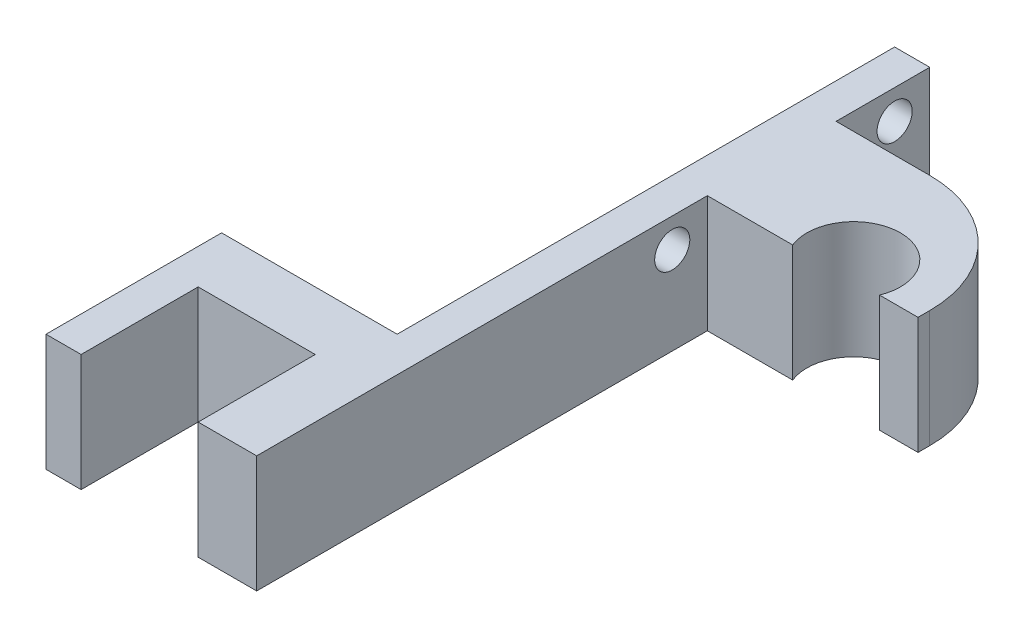
SolidWorks part; units mm, degrees
ref_plane "Front Plane" through (0, 0, 0) normal (0, 0, 1) x (1, 0, 0)
ref_plane "Top Plane" through (0, 0, 0) normal (0, 1, 0) x (1, 0, 0)
ref_plane "Right Plane" through (0, 0, 0) normal (1, 0, 0) x (0, 0, -1)
sketch "Sketch1" plane through (0, 0, 0) normal (0, 1, 0) x (1, 0, 0)
  line L0 (0, 0) -> (0, 34)
  line L1 (5, 34.5) -> (23, 34.5)
  line L2 (23, 23.5) -> (23, 34.5)
  line L3 (23, 23.5) -> (5, 23.5)
  line L4 (5, 23.5) -> (5, -15)
  line L5 (5, -15) -> (0, -15)
  line L6 (0, -15) -> (0, -5)
  line L7 (0, -5) -> (-10, -5)
  line L8 (-10, -5) -> (-10, -15)
  line L9 (-10, -15) -> (-13, -15)
  line L10 (-13, -15) -> (-13, 0)
  line L11 (-13, 0) -> (0, 0)
  line L12 (23, 29) -> (0, 29) construction
  line L13 (5, 23.5) -> (5, 42.5) construction
  line L14 (5, 42.5) -> (0, 42.5) construction
  line L15 (0, 42.5) -> (0, 34) construction
  line L16 (5, 34.5) -> (5, 42.5)
  line L17 (5, 42.5) -> (0, 42.5)
  line L18 (0, 42.5) -> (0, 34)
  dimension "D1" = 10
  dimension "D2" = 3
  dimension "D3" = 5
  dimension "D4" = 10
  dimension "D5" = 5
  dimension "D6" = 11
  dimension "D7" = 34
  dimension "D8" = 23
  dimension "D9" = 8
extrude "Boss-Extrude1" add sketch "Sketch1" along normal blind 10
sketch "Sketch2" plane through (0, 10, 0) normal (0, 1, 0) x (1, 0, 0)
  line L0 (-10, -5) -> (0, -5) construction
  line L3 (0, -5) -> (0, -15) construction
  circle A0 centre (16, 25) radius 4
  dimension "D1" = 8
  dimension "D2" = 16
  dimension "D3" = 30
extrude "Cut-Extrude1" cut sketch "Sketch2" against normal through all
sketch "Sketch3" plane through (0, 0, 0) normal (-1, 0, 0) x (0, 0, 1)
  line L0 (-34.5, 7.5) -> (15, 7.5) construction
  line L1 (-34.5, 10) -> (-34.5, 0) construction
  line L2 (15, 10) -> (15, 0) construction
  line L3 (-42.5, 10) -> (0, 10) construction
  circle A0 centre (-39.5, 7.5) radius 1.5
  circle A1 centre (-20.5, 7.5) radius 1.5
  dimension "D2" = 3
  dimension "D3" = 3
  dimension "D1" = 2.5
  dimension "D4" = 19
  dimension "D5" = 5
extrude "Cut-Extrude2" cut sketch "Sketch3" against normal through all
sketch "Sketch5" plane through (0, 0, 0) normal (-1, 0, 0) x (0, 0, 1)
  line L0 (-42.5, 10) -> (-42.5, 0) construction
  line L1 (-42.5, 10) -> (0, 10)
  line L2 (-42.5, 10) -> (-42.5, 0)
  line L3 (-42.5, 0) -> (0, 0)
  line L4 (0, 10) -> (0, 0)
  dimension "D1" = 0
extrude "Cut-Extrude4" cut sketch "Sketch5" against normal blind 2
fillet "Fillet1" radius 10 1 edges at (23, 5, -34.5)
equation "\"X-ROD-SPACING\"=45"
equation "\"Y-ROD-SPACING\"=75"
equation "\"Z-ROD-SPACING\"=17.5"
equation "\"Y-BED-OFFSET\"=2"
equation "\"Y-BED-ROD-INSET\"=3.5"
equation "\"Y-BED-SCREW-SPACING\"=209"
equation "\"Y-BED-SCREW-CUTOUT-SLOT-HEIGHT\"=1"
equation "\"T-SLOT-NUT-FILLET-RADIUS\"=0.25"
equation "\"T-SLOT-SCREW-SHAFT-RADIUS\"=1.75"
equation "\"T-SLOT-SCREW-SHAFT-CUTOUT-LENGTH\"=10.5"
equation "\"T-SLOT-NUT-DEPTH\"=4.2"
equation "\"T-SLOT-NUT-WIDTH\"=3"
equation "\"T-SLOT-NUT-END-DISTANCE\"=8"
equation "\"ACRYLIC-THICKNESS\"=10"
equation "\"ACRYLIC-THICKNESS2\"=4.5"
equation "\"ACRYLIC-TAB-CUTOUT-SIZE\"=\"ACRYLIC-THICKNESS\"+\"ACRYLIC-TAB-TOLERANCE\"*2"
equation "\"ACRYLIC-TAB-WIDTH\"=\"ACRYLIC-THICKNESS\""
equation "\"ACRYLIC-M3-HOLE\"=3.2"
equation "\"SMOOTHROD-CAP-SCREW-DISTANCE\"=20"
equation "\"FRAME-WIDTH-INNER\"=370"
equation "\"NEMA17-HOLE-SPACING\"=31"
equation "\"NEMA17-CENTRAL-CUTOUT\"=22.5"
equation "\"Z-BRACKET-REACH\"=55"
equation "\"Z-ROD-INSET\"=16"
equation "\"TOP-BRACKET-SPACING\"=40"
equation "\"SMOOTHROD-X-LENGTH\"=350"
equation "\"SMOOTHROD-Y-LENGTH\"=350"
equation "\"SMOOTHROD-Z-LENGTH\"=350"
equation "\"SMOOTHROD-TIGHTENING-HEADROOM\"=1"
equation "\"LEADSCREW-Z-LENGTH\"=300"
equation "\"SCREW-LENGTH-FRAME\"=\"ACRYLIC-THICKNESS\" + 10"
equation "\"SCREW-LENGTH-MOTOR\"=\"ACRYLIC-THICKNESS\" + 5"
equation "\"SCREW-HEAD-RADIUS\"=6"
equation "\"PRINTED-X-SMOOTHROD-DIAMETER\"=8.2"
equation "\"PRINTED-X-SMOOTHROD-CUTOUT\"=10"
equation "\"PRINTED-X-BASE-HEIGHT\"=10"
equation "\"PRINTED-LM8UU-CUTOUT-SIZE\"=16"
equation "\"PRINTED-LM8UU-CUTOUT-LENGTH\"=24.5"
equation "\"PRINTED-X-IDLER-HEIGHT\"=16"
equation "\"PSU-MOUNTING-WIDTH\"=95"
equation "\"PSU-MOUNTING-HEIGHT\"=177"
equation "\"Y-BELT-TO-ROD-DISTANCE\"=20"
equation "\"SPOOL-HOLDER-ROD-SPACING\"=150"
equation "\"D1@Sketch1\"=\"ACRYLIC-THICKNESS\""
equation "\"D2@Sketch2\"=\"Z-ROD-INSET\""
equation "\"D8@Sketch1\"=\"Z-ROD-INSET\"+7"
